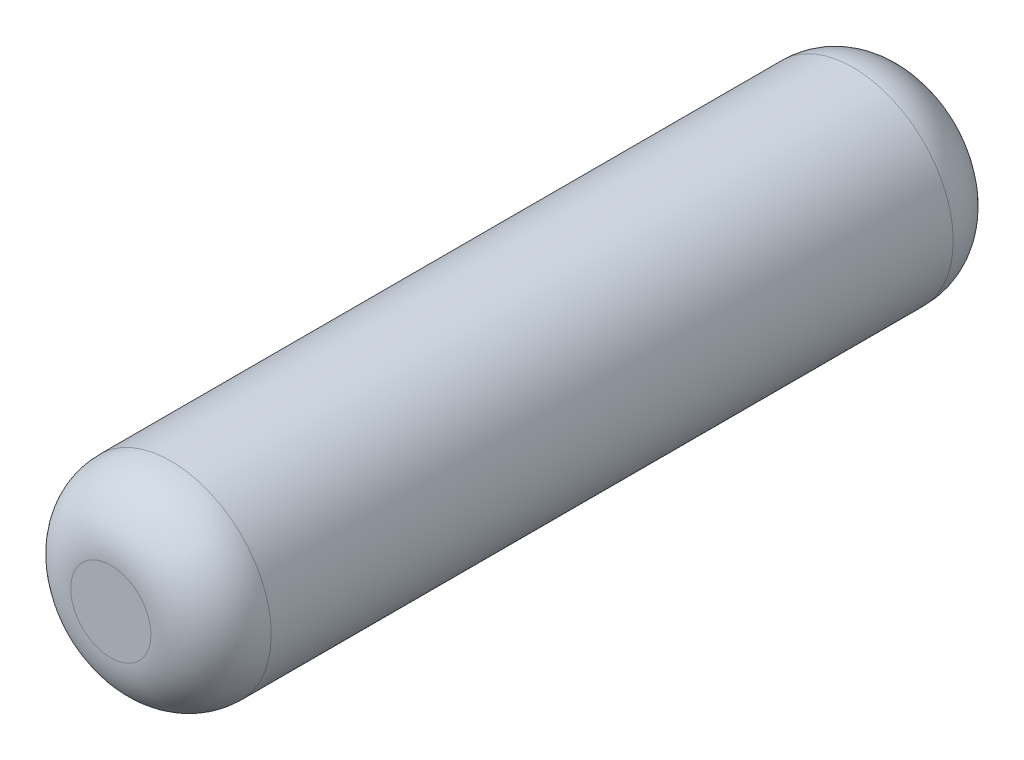
SolidWorks part; units mm, degrees
ref_plane "Front Plane" through (0, 0, 0) normal (0, 0, 1) x (1, 0, 0)
ref_plane "Top Plane" through (0, 0, 0) normal (0, 1, 0) x (1, 0, 0)
ref_plane "Right Plane" through (0, 0, 0) normal (1, 0, 0) x (0, 0, -1)
sketch "Sketch1" plane through (0, 0, 0) normal (0, 0, 1) x (1, 0, 0)
  circle A0 centre (0, 0) radius 5
  dimension "D1" = 10
extrude "Boss-Extrude1" add sketch "Sketch1" along normal blind 40
fillet "Fillet3" radius 3 1 edges at (5, 0, 40)
fillet "Fillet4" radius 3 1 edges at (5, 0, 0)
